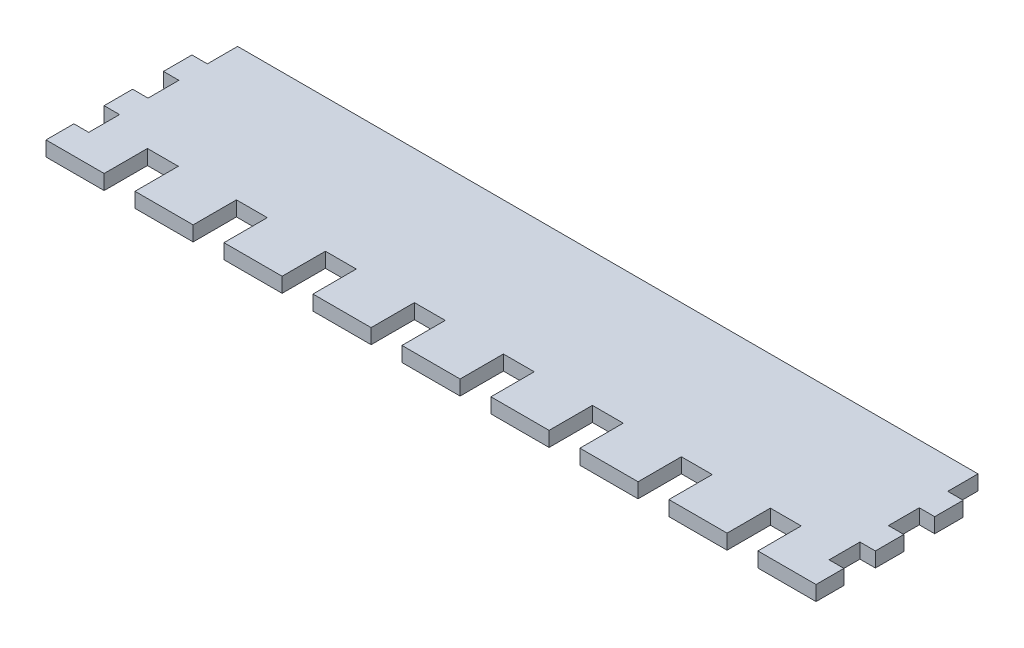
SolidWorks part; units mm, degrees
ref_plane "Front Plane" through (0, 0, 0) normal (0, 0, 1) x (1, 0, 0)
ref_plane "Top Plane" through (0, 0, 0) normal (0, 1, 0) x (1, 0, 0)
ref_plane "Right Plane" through (0, 0, 0) normal (1, 0, 0) x (0, 0, -1)
sketch "Sketch1" plane through (0, 0, 0) normal (0, 1, 0) x (1, 0, 0)
  line L2 (-165.1, -28.575) -> (-165.1, 28.575)
  line L3 (-165.1, 28.575) -> (165.1, 28.575)
  line L4 (165.1, -28.575) -> (165.1, 28.575)
  line L5 (-165.1, -28.575) -> (165.1, 28.575) construction
  line L6 (-165.1, 28.575) -> (165.1, -28.575) construction
  line L11 (-165.1, -28.575) -> (165.1, -28.575)
  point P0 (0, 0)
  dimension "D1" = 57.15
  dimension "D2" = 330.2
extrude "Boss-Extrude1" add sketch "Sketch1" along normal blind 6.35
sketch "Sketch3" plane through (0, 0, 0) normal (0, 1, 0) x (1, 0, 0)
  line L0 (-165.1, -28.575) -> (165.1, -28.575) construction
  line L1 (-126.746, -28.575) -> (-126.746, -47.117)
  line L2 (-126.746, -47.117) -> (-101.854, -47.117)
  line L3 (-101.854, -47.117) -> (-101.854, -28.575)
  line L4 (-101.854, -28.575) -> (-126.746, -28.575)
  line L25 (-63.754, -47.117) -> (-63.754, -28.575)
  line L26 (-63.754, -28.575) -> (-88.646, -28.575)
  line L27 (-88.646, -28.575) -> (-88.646, -47.117)
  line L28 (-88.646, -47.117) -> (-63.754, -47.117)
  line L29 (-25.654, -47.117) -> (-25.654, -28.575)
  line L30 (-25.654, -28.575) -> (-50.546, -28.575)
  line L31 (-50.546, -28.575) -> (-50.546, -47.117)
  line L32 (-50.546, -47.117) -> (-25.654, -47.117)
  line L33 (12.446, -47.117) -> (12.446, -28.575)
  line L34 (12.446, -28.575) -> (-12.446, -28.575)
  line L35 (-12.446, -28.575) -> (-12.446, -47.117)
  line L36 (-12.446, -47.117) -> (12.446, -47.117)
  line L37 (50.546, -47.117) -> (50.546, -28.575)
  line L38 (50.546, -28.575) -> (25.654, -28.575)
  line L39 (25.654, -28.575) -> (25.654, -47.117)
  line L40 (25.654, -47.117) -> (50.546, -47.117)
  line L41 (88.646, -47.117) -> (88.646, -28.575)
  line L42 (88.646, -28.575) -> (63.754, -28.575)
  line L43 (63.754, -28.575) -> (63.754, -47.117)
  line L44 (63.754, -47.117) -> (88.646, -47.117)
  line L45 (126.746, -47.117) -> (126.746, -28.575)
  line L46 (126.746, -28.575) -> (101.854, -28.575)
  line L47 (101.854, -28.575) -> (101.854, -47.117)
  line L48 (101.854, -47.117) -> (126.746, -47.117)
  line L49 (164.846, -47.117) -> (164.846, -28.575)
  line L50 (164.846, -28.575) -> (139.954, -28.575)
  line L51 (139.954, -28.575) -> (139.954, -47.117)
  line L52 (139.954, -47.117) -> (164.846, -47.117)
  line L53 (-164.846, -28.575) -> (-164.846, -47.117)
  line L54 (-164.846, -47.117) -> (-139.954, -47.117)
  line L55 (-139.954, -47.117) -> (-139.954, -28.575)
  line L56 (-139.954, -28.575) -> (-164.846, -28.575)
  point P0 (-114.3, -28.575)
  point P37 (-152.4, -28.575)
  dimension "D1" = 24.892
  dimension "D2" = 18.542
  dimension "D3" = 50.8
  dimension "D4" = 8
  dimension "D5" = 2
extrude "Boss-Extrude2" add sketch "Sketch3" along normal blind 6.35
sketch "Sketch4" plane through (0, 0, 0) normal (0, 1, 0) x (1, 0, 0)
  line L0 (165.1, 28.575) -> (-165.1, 28.575) construction
  line L8 (0, 0) -> (0, 63.6475) construction
  line L13 (165.1, -28.575) -> (165.1, 28.575) construction
  line L14 (158.496, 28.829) -> (171.704, 28.829)
  line L30 (158.496, 28.829) -> (158.496, 15.621)
  line L31 (158.496, 15.621) -> (171.704, 15.621)
  line L32 (171.704, 28.829) -> (171.704, 15.621)
  line L33 (158.496, 28.829) -> (171.704, 15.621) construction
  line L34 (158.496, 15.621) -> (171.704, 28.829) construction
  line L35 (-158.496, -35.179) -> (-171.704, -21.971) construction
  line L38 (-158.496, -21.971) -> (-171.704, -35.179) construction
  line L39 (-158.496, -9.779) -> (-171.704, 3.429) construction
  line L44 (-158.496, 3.429) -> (-171.704, -9.779) construction
  line L45 (-158.496, 15.621) -> (-171.704, 28.829) construction
  line L50 (-158.496, 28.829) -> (-171.704, 15.621) construction
  line L51 (-171.704, -21.971) -> (-171.704, -35.179)
  line L52 (158.496, 3.429) -> (171.704, 3.429)
  line L53 (158.496, 3.429) -> (158.496, -9.779)
  line L54 (158.496, -9.779) -> (171.704, -9.779)
  line L55 (171.704, 3.429) -> (171.704, -9.779)
  line L56 (158.496, 3.429) -> (171.704, -9.779) construction
  line L57 (158.496, -9.779) -> (171.704, 3.429) construction
  line L58 (158.496, -21.971) -> (171.704, -21.971)
  line L59 (158.496, -21.971) -> (158.496, -35.179)
  line L60 (158.496, -35.179) -> (171.704, -35.179)
  line L61 (171.704, -21.971) -> (171.704, -35.179)
  line L62 (158.496, -21.971) -> (171.704, -35.179) construction
  line L63 (158.496, -35.179) -> (171.704, -21.971) construction
  line L64 (-108.204, 28.829) -> (-94.996, 28.829) [skipped]
  line L65 (-108.204, 28.829) -> (-108.204, 15.621) [skipped]
  line L66 (-108.204, 15.621) -> (-94.996, 15.621) [skipped]
  line L67 (-94.996, 28.829) -> (-94.996, 15.621) [skipped]
  line L68 (-108.204, 3.429) -> (-94.996, 3.429) [skipped]
  line L69 (-108.204, 3.429) -> (-108.204, -9.779) [skipped]
  line L70 (-108.204, -9.779) -> (-94.996, -9.779) [skipped]
  line L71 (-94.996, 3.429) -> (-94.996, -9.779) [skipped]
  line L72 (-108.204, -21.971) -> (-94.996, -21.971) [skipped]
  line L73 (-108.204, -21.971) -> (-108.204, -35.179) [skipped]
  line L74 (-108.204, -35.179) -> (-94.996, -35.179) [skipped]
  line L75 (-94.996, -21.971) -> (-94.996, -35.179) [skipped]
  line L76 (-108.204, 28.829) -> (-94.996, 15.621) construction
  line L77 (-108.204, 15.621) -> (-94.996, 28.829) construction
  line L78 (-108.204, 3.429) -> (-94.996, -9.779) construction
  line L79 (-108.204, -9.779) -> (-94.996, 3.429) construction
  line L80 (-108.204, -21.971) -> (-94.996, -35.179) construction
  line L81 (-108.204, -35.179) -> (-94.996, -21.971) construction
  line L82 (-158.496, -35.179) -> (-171.704, -35.179)
  line L83 (-158.496, -21.971) -> (-158.496, -35.179)
  line L84 (-158.496, -21.971) -> (-171.704, -21.971)
  line L85 (-171.704, 3.429) -> (-171.704, -9.779)
  line L86 (-158.496, -9.779) -> (-171.704, -9.779)
  line L87 (-158.496, 3.429) -> (-158.496, -9.779)
  line L88 (-158.496, 3.429) -> (-171.704, 3.429)
  line L89 (-171.704, 28.829) -> (-171.704, 15.621)
  line L90 (-158.496, 15.621) -> (-171.704, 15.621)
  line L91 (-158.496, 28.829) -> (-158.496, 15.621)
  line L92 (-158.496, 28.829) -> (-171.704, 28.829)
  point P0 (-101.6, -28.575)
  point P1 (-101.6, -3.175)
  point P5 (-101.6, 22.225)
  point P13 (165.1, 22.225)
  point P27 (-165.1, -28.575)
  point P28 (-165.1, -3.175)
  point P29 (165.1, -3.175)
  point P34 (165.1, -28.575)
  point P36 (-165.1, 22.225)
  dimension "D1" = 3
  dimension "D2" = 2
  dimension "D4" = 13.208
  dimension "D6" = 13.208
  dimension "D7" = 6.35
extrude "Cut-Extrude2" cut sketch "Sketch4" along normal through all
